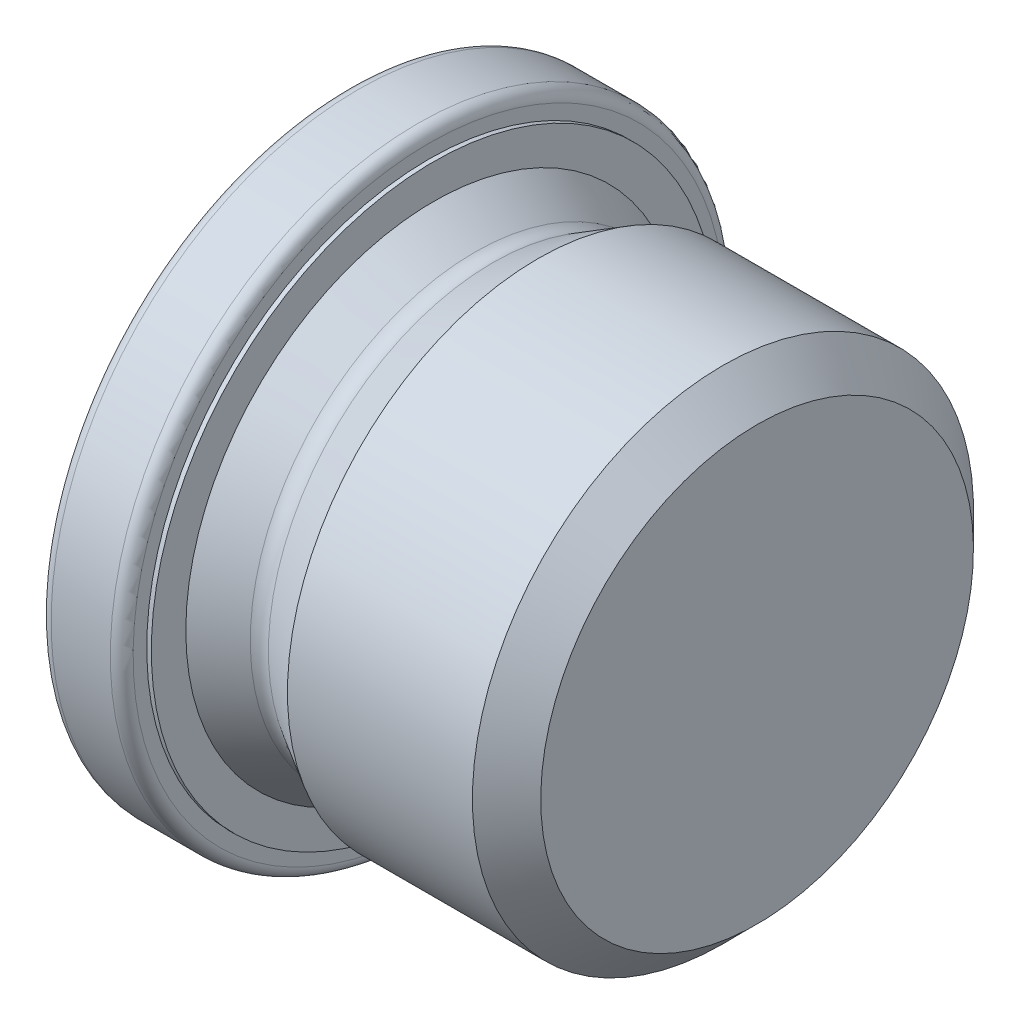
SolidWorks part; units mm, degrees
material "4140 H/T"
ref_plane "Front Plane" through (0, 0, 0) normal (0, 0, 1) x (1, 0, 0)
ref_plane "Top Plane" through (0, 0, 0) normal (0, 1, 0) x (1, 0, 0)
ref_plane "Right Plane" through (0, 0, 0) normal (1, 0, 0) x (0, 0, -1)
sketch "Sketch1" plane through (0, 0, 0) normal (0, 0, 1) x (1, 0, 0)
  line L0 (0, 0) -> (0, 9.5)
  line L1 (0, 9.5) -> (-1.5, 11)
  line L2 (-1.5, 11) -> (-9.6225, 11)
  line L3 (-9.6225, 11) -> (-11.6019, 9.8572)
  line L4 (-12.3991, 9.8556) -> (-14.4, 11)
  line L5 (-14.4, 11) -> (-14.4, 13.5)
  line L6 (-14.4, 13.5) -> (-18, 13.5)
  line L7 (-18, 13.5) -> (-18, 0)
  line L8 (0, 0) -> (-18, 0) construction
  line L9 (0, 0) -> (-18, 0)
  arc A0 (-11.6019, 9.8572) -> (-12.3991, 9.8556) centre (-12.0019, 10.55) cw
  point P12 (-12, 9.6273)
  dimension "D11" = 0.8
  dimension "D1" = 18
  dimension "D2" = 27
  dimension "D3" = 22
  dimension "D4" = 30
  dimension "D5" = 19.5
  dimension "D6" = 3.6
  dimension "D7" = 22
  dimension "D8" = 12
  dimension "D9" = 45
  dimension "D10" = 19
revolve "Revolve1" add sketch "Sketch1" angle 360 about L8
cosmetic thread "Cosmetic Thread1" parameters "D1"=11.6019, "D2"=20
sketch "Sketch2" plane through (-18, 0, 0) normal (-1, 0, 0) x (0, 0, 1)
  line L1 (-4.8, -4.8) -> (4.8, -4.8)
  line L2 (4.8, -4.8) -> (4.8, 4.8)
  line L3 (4.8, 4.8) -> (-4.8, 4.8)
  line L4 (-4.8, 4.8) -> (-4.8, -4.8)
  circle A0 centre (0, 0) radius 4.8 construction
  dimension "D1" = 9.6
extrude "Cut-Extrude1" cut sketch "Sketch2" against normal blind 10
fillet "Fillet1" radius 0.5 2 edges at (-18, 13.5, 0) (-14.4, 13.5, 0)
sketch "Sketch3" plane through (0, 0, 0) normal (0, 0, 1) x (1, 0, 0)
  line L1 (-15.7, 10.4) -> (-14.2, 10.4)
  line L2 (-15.7, 10.4) -> (-15.7, 12.4)
  line L3 (-15.7, 12.4) -> (-14.2, 12.4)
  line L4 (-14.2, 10.4) -> (-14.2, 12.4)
  line L5 (0, 0) -> (-27.0744, 0) construction
  line L6 (-14.4, -13) -> (-14.4, 13) construction
  dimension "D1" = 24.8
  dimension "D2" = 1.5
  dimension "D3" = 0.2
  dimension "D4" = 20.8
revolve "Revolve2" add sketch "Sketch3" angle 360 about L5
